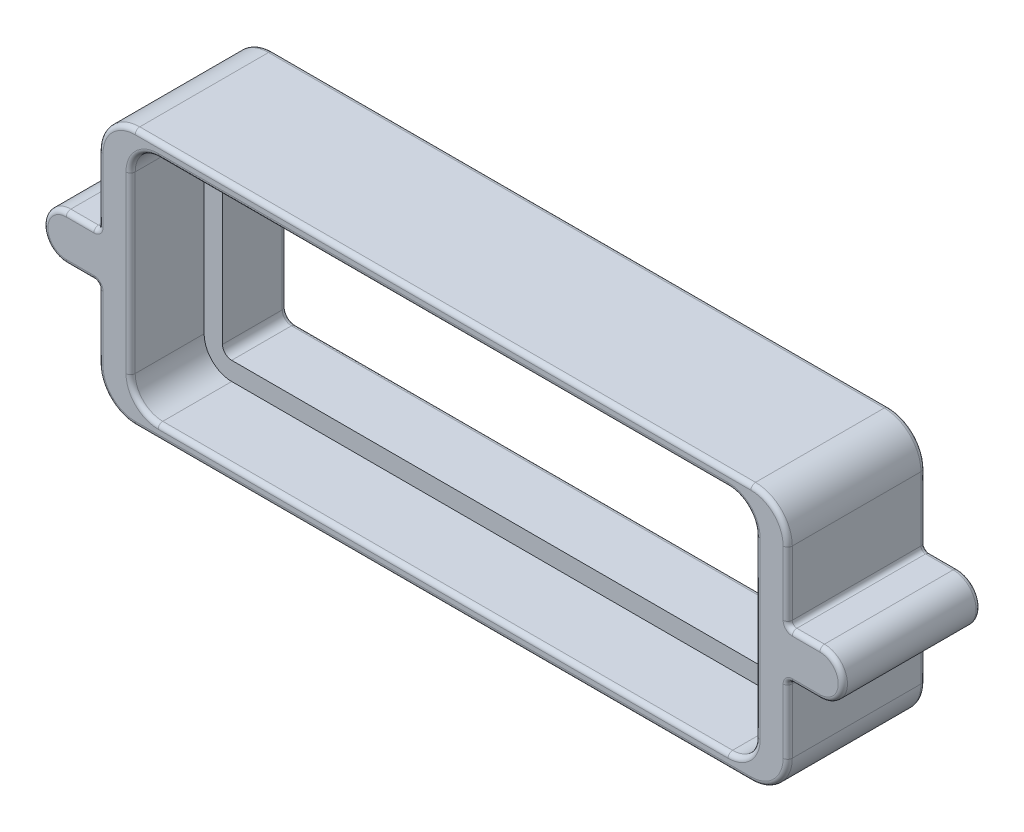
SolidWorks part; units mm, degrees
ref_plane "Front" through (0, 0, 0) normal (0, 0, 1) x (1, 0, 0)
ref_plane "Top" through (0, 0, 0) normal (0, 1, 0) x (1, 0, 0)
ref_plane "Right" through (0, 0, 0) normal (1, 0, 0) x (0, 0, -1)
sketch "Esquisse1" plane through (0, 0, 0) normal (0, 0, 1) x (1, 0, 0)
  line L1 (-37.5, -14) -> (37.5, -14)
  line L2 (-37.5, -14) -> (-37.5, 14)
  line L3 (-37.5, 14) -> (37.5, 14)
  line L4 (37.5, -14) -> (37.5, 14)
  line L5 (-37.5, -14) -> (37.5, 14) construction
  line L6 (-37.5, 14) -> (37.5, -14) construction
  point P0 (0, 0)
  dimension "D1" = 75
  dimension "D2" = 28
extrude "Boss.-Extru.1" add sketch "Esquisse1" along normal blind 15
fillet "Congé1" radius 4 4 edges at (37.5, -14, 7.5) (-37.5, 14, 7.5) (37.5, 14, 7.5) (-37.5, -14, 7.5)
sketch "Esquisse2" plane through (0, 0, 15) normal (0, 0, 1) x (1, 0, 0)
  line L0 (-41, 0) -> (41, 0) construction
  line L1 (-41, 2.5) -> (41, 2.5)
  line L2 (-41, -2.5) -> (41, -2.5)
  arc A0 (-41, 2.5) -> (-41, -2.5) centre (-41, 0) ccw
  arc A1 (41, -2.5) -> (41, 2.5) centre (41, 0) ccw
  point P2 (0, 0)
  dimension "D1" = 5
  dimension "D2" = 82
extrude "Boss.-Extru.2" add sketch "Esquisse2" against normal up to surface (15 mm away) up to face at (0, 0, 0)
fillet "Congé2" radius 0.5 4 edges at (37.5, 2.5, 7.5) (37.5, -2.5, 7.5) (-37.5, 2.5, 7.5) (-37.5, -2.5, 7.5)
sketch "Esquisse3" plane through (0, 0, 15) normal (0, 0, 1) x (1, 0, 0)
  line L1 (-31, 12.5) -> (31, 12.5)
  line L2 (-34, 9.5) -> (-34, -9.5)
  line L3 (-31, -12.5) -> (31, -12.5)
  line L4 (34, 9.5) -> (34, -9.5)
  line L5 (0, -12.5) -> (0, 12.5) construction
  line L6 (-34, 0) -> (34, 0) construction
  arc A0 (31, 12.5) -> (34, 9.5) centre (31, 9.5) cw
  arc A1 (31, -12.5) -> (34, -9.5) centre (31, -9.5) ccw
  arc A2 (-34, -9.5) -> (-31, -12.5) centre (-31, -9.5) ccw
  arc A3 (-31, 12.5) -> (-34, 9.5) centre (-31, 9.5) ccw
  point P48 (0, 0)
  dimension "D1" = 3
  dimension "D2" = 25
  dimension "D3" = 68
extrude "Enlèv. mat.-Extru.1" cut sketch "Esquisse3" against normal blind 8
sketch "Esquisse4" plane through (0, 0, 7) normal (0, 0, 1) x (1, 0, 0)
  line L12 (31, 10.5) -> (-31, 10.5)
  line L13 (-32, 9.5) -> (-32, -9.5)
  line L14 (-31, -10.5) -> (31, -10.5)
  line L15 (32, -9.5) -> (32, 9.5)
  line L16 (31, 10.5) -> (-31, 10.5)
  line L17 (-32, 9.5) -> (-32, -9.5)
  line L18 (-31, -10.5) -> (31, -10.5)
  line L19 (32, -9.5) -> (32, 9.5)
  arc A12 (32, 9.5) -> (31, 10.5) centre (31, 9.5) ccw
  arc A13 (-31, 10.5) -> (-32, 9.5) centre (-31, 9.5) ccw
  arc A14 (-32, -9.5) -> (-31, -10.5) centre (-31, -9.5) ccw
  arc A15 (31, -10.5) -> (32, -9.5) centre (31, -9.5) ccw
  arc A16 (32, 9.5) -> (31, 10.5) centre (31, 9.5) ccw
  arc A17 (-31, 10.5) -> (-32, 9.5) centre (-31, 9.5) ccw
  arc A18 (-32, -9.5) -> (-31, -10.5) centre (-31, -9.5) ccw
  arc A19 (31, -10.5) -> (32, -9.5) centre (31, -9.5) ccw
  dimension "D1" = 2
extrude "Enlèv. mat.-Extru.2" cut sketch "Esquisse4" against normal through all
fillet "Congé3" radius 0.5 56 edges at (36.3284, 12.8284, 0) (0, 14, 0) (-36.3284, 12.8284, 0) (-37.5, 6.5, 0) (-37.6464, 2.6464, 0) (-39.5, 2.5, 15) (-39.5, 2.5, 0) (-43.5, 0, 0) (-43.5, 0, 15) (-39.5, -2.5, 0) (-39.5, -2.5, 15) (-37.6464, -2.6464, 0) (-37.5, -6.5, 0) (-36.3284, -12.8284, 0) (0, -14, 0) (36.3284, -12.8284, 0) (37.5, -6.5, 0) (37.6464, -2.6464, 0) (39.5, -2.5, 15) (39.5, -2.5, 0) (43.5, 0, 0) (43.5, 0, 15) (39.5, 2.5, 0) (39.5, 2.5, 15) (37.6464, 2.6464, 0) (37.5, 6.5, 0) (32, 0, 0) (31.7071, -10.2071, 0) (0, -10.5, 0) (-31.7071, -10.2071, 0) (-32, 0, 0) (-31.7071, 10.2071, 0) (0, 10.5, 0) (31.7071, 10.2071, 0) (-36.3284, 12.8284, 15) (0, 14, 15) (36.3284, 12.8284, 15) (37.5, 6.5, 15) (37.6464, 2.6464, 15) (37.6464, -2.6464, 15) (37.5, -6.5, 15) (36.3284, -12.8284, 15) (0, -14, 15) (-36.3284, -12.8284, 15) (-37.5, -6.5, 15) (-37.6464, -2.6464, 15) (-37.6464, 2.6464, 15) (-37.5, 6.5, 15) (-33.1213, 11.6213, 15) (-34, 0, 15) (-33.1213, -11.6213, 15) (0, -12.5, 15) (33.1213, -11.6213, 15) (34, 0, 15) (33.1213, 11.6213, 15) (0, 12.5, 15)
